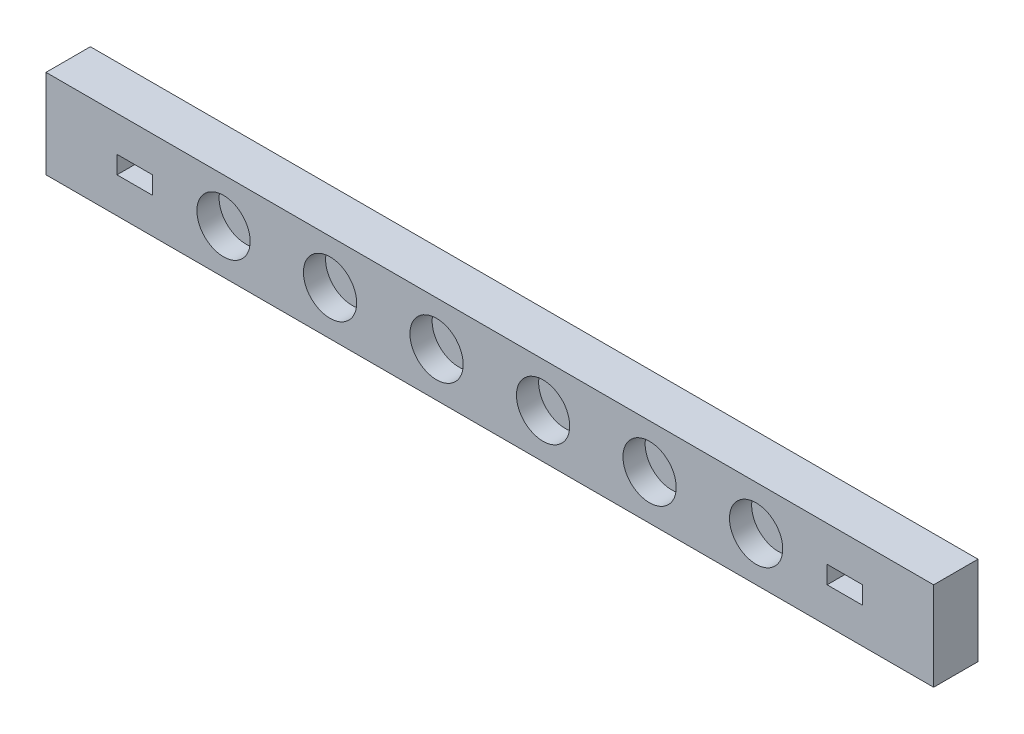
SolidWorks part; units mm, degrees
ref_plane "Front Plane" through (0, 0, 0) normal (0, 0, 1) x (1, 0, 0)
ref_plane "Top Plane" through (0, 0, 0) normal (0, 1, 0) x (1, 0, 0)
ref_plane "Right Plane" through (0, 0, 0) normal (1, 0, 0) x (0, 0, -1)
sketch "Sketch1" plane through (0, 0, 0) normal (0, 0, 1) x (1, 0, 0)
  line L1 (-450, 50) -> (450, 50)
  line L2 (-450, 50) -> (-450, -50)
  line L3 (-450, -50) -> (450, -50)
  line L4 (450, 50) -> (450, -50)
  line L5 (-450, 50) -> (450, -50) construction
  line L6 (-450, -50) -> (450, 50) construction
  point P0 (0, 0)
  dimension "D1" = 900
  dimension "D2" = 100
extrude "Boss-Extrude1" add sketch "Sketch1" along normal blind 50
sketch "Sketch2" plane through (0, 0, 50) normal (0, 0, 1) x (1, 0, 0)
  line L0 (-450, 50) -> (-450, -50) construction
  line L1 (450, 50) -> (-450, 50) construction
  line L2 (-420, 10) -> (-380, 10)
  line L3 (-420, 10) -> (-420, -10)
  line L4 (-420, -10) -> (-380, -10)
  line L5 (-380, 10) -> (-380, -10)
  line L6 (-420, 10) -> (-380, -10) construction
  line L7 (-420, -10) -> (-380, 10) construction
  line L9 (0, 50) -> (0, -50)
  line L10 (-450, -50) -> (450, -50) construction
  line L11 (380, 10) -> (380, -10)
  line L12 (420, 10) -> (380, 10)
  line L13 (420, 10) -> (420, -10)
  line L14 (420, -10) -> (380, -10)
  circle A0 centre (-300, 0) radius 30
  circle A1 centre (-180, 0) radius 30
  circle A2 centre (-60, 0) radius 30
  circle A3 centre (60, 0) radius 30
  circle A4 centre (180, 0) radius 30
  circle A5 centre (300, 0) radius 30
  point P14 (-400, 0)
  dimension "D1" = 6
  dimension "D2" = 150
  dimension "D3" = 40
  dimension "D4" = 20
  dimension "D5" = 50
  dimension "D6" = 40
extrude "Cut-Extrude1" cut sketch "Sketch2" against normal blind 25 contours A0 | A1 | A2 | A3 | A4 | A5 | L14 L13 L12 L11 | L3 L2 L5 L4
sketch "Sketch3" plane through (0, 50, 0) normal (0, 1, 0) x (1, 0, 0)
  line L1 (450, 0) -> (500, 0)
  line L2 (450, 0) -> (450, -50)
  line L3 (450, -50) -> (500, -50)
  line L4 (500, 0) -> (500, -50)
  line L6 (-450, 0) -> (-500, 0)
  line L7 (-450, 0) -> (-450, -50)
  line L8 (-450, -50) -> (-500, -50)
  line L9 (-500, 0) -> (-500, -50)
  dimension "D1" = 50
  dimension "D2" = 50
extrude "Boss-Extrude3" add sketch "Sketch3" against normal blind 100
